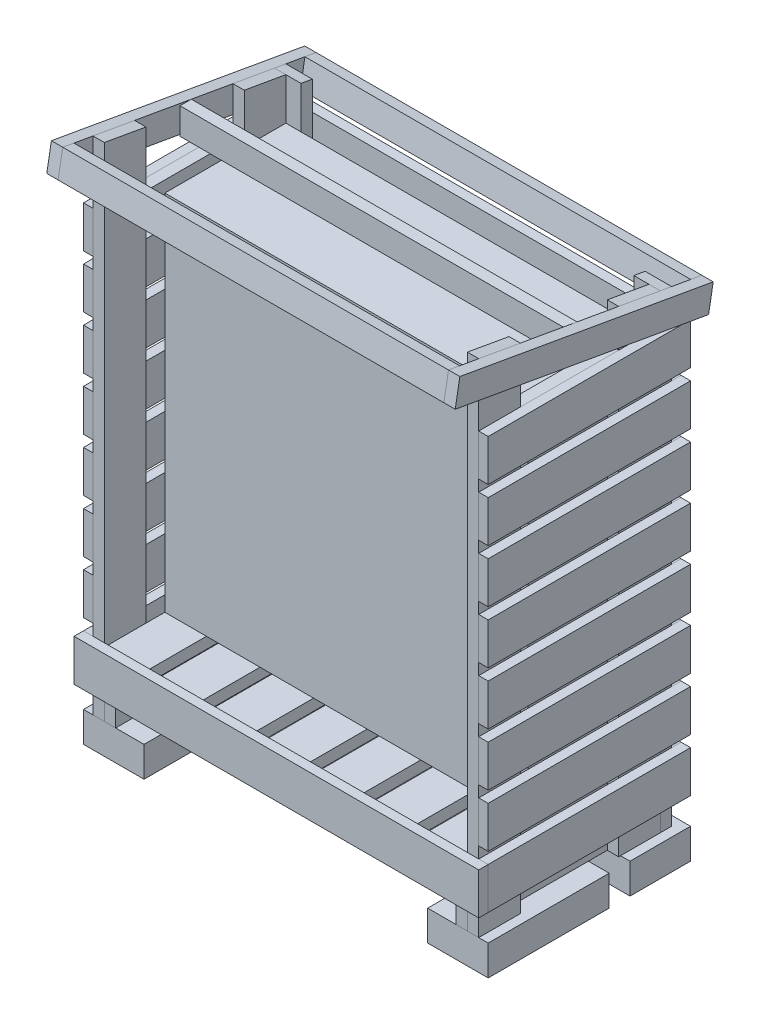
SolidWorks part; units mm, degrees
other "Wood"
ref_plane "Front Plane" through (0, 0, 0) normal (0, 0, 1) x (1, 0, 0)
ref_plane "Top Plane" through (0, 0, 0) normal (0, 1, 0) x (1, 0, 0)
ref_plane "Right Plane" through (0, 0, 0) normal (1, 0, 0) x (0, 0, -1)
sketch "Sketch4" plane through (0, 0, 0) normal (0, 1, 0) x (1, 0, 0)
  line L0 (-609.6, 304.8) -> (609.6, -304.8) construction
  line L1 (-609.6, 304.8) -> (609.6, 304.8)
  line L2 (-609.6, 304.8) -> (-609.6, 266.7)
  line L3 (-609.6, 266.7) -> (609.6, 266.7)
  line L4 (609.6, 304.8) -> (609.6, 266.7)
  line L5 (-609.6, -266.7) -> (609.6, -266.7)
  line L6 (-609.6, -266.7) -> (-609.6, -304.8)
  line L7 (-609.6, -304.8) -> (609.6, -304.8)
  line L8 (609.6, -266.7) -> (609.6, -304.8)
  line L10 (609.6, 304.8) -> (571.5, 304.8)
  line L11 (609.6, 304.8) -> (609.6, -304.8)
  line L12 (609.6, -304.8) -> (571.5, -304.8)
  line L13 (571.5, 304.8) -> (571.5, -304.8)
  line L14 (-609.6, 304.8) -> (-571.5, 304.8)
  line L15 (-609.6, 304.8) -> (-609.6, -304.8)
  line L16 (-609.6, -304.8) -> (-571.5, -304.8)
  line L17 (-571.5, 304.8) -> (-571.5, -304.8)
  point P8 (0, 0)
  dimension "D1" = 609.6
  dimension "D2" = 38.1
  dimension "D3" = 1219.2
sketch "Sketch5" plane through (0, 0, 0) normal (0, 1, 0) x (1, 0, 0)
  line L0 (-609.6, 304.8) -> (-571.5, 304.8) construction
  line L1 (-609.6, -304.8) -> (-571.5, -304.8) construction
  line L2 (609.6, -304.8) -> (571.5, -304.8) construction
  line L3 (609.6, 304.8) -> (571.5, 304.8) construction
  line L4 (609.6, 304.8) -> (609.6, -304.8) construction
  line L5 (571.5, 304.8) -> (571.5, -304.8) construction
  line L6 (-609.6, 304.8) -> (-609.6, -304.8) construction
  line L7 (-571.5, 304.8) -> (-571.5, -304.8) construction
  line L8 (-609.6, 304.8) -> (-571.5, 304.8)
  line L9 (-609.6, -304.8) -> (-571.5, -304.8)
  line L10 (609.6, -304.8) -> (571.5, -304.8)
  line L11 (609.6, 304.8) -> (571.5, 304.8)
  line L12 (609.6, 304.8) -> (609.6, -304.8)
  line L13 (571.5, 304.8) -> (571.5, -304.8)
  line L14 (-609.6, 304.8) -> (-609.6, -304.8)
  line L15 (-571.5, 304.8) -> (-571.5, -304.8)
extrude "Boss-Extrude2" add sketch "Sketch5" against normal blind 88.9
sketch "Sketch6" plane through (0, 0, 0) normal (0, 1, 0) x (1, 0, 0)
  line L0 (-609.6, -266.7) -> (-609.6, -304.8) construction
  line L1 (-609.6, -304.8) -> (609.6, -304.8) construction
  line L2 (-609.6, -266.7) -> (609.6, -266.7) construction
  line L3 (609.6, -266.7) -> (609.6, -304.8) construction
  line L4 (609.6, 304.8) -> (609.6, 266.7) construction
  line L5 (-609.6, 304.8) -> (-609.6, 266.7) construction
  line L6 (-609.6, 266.7) -> (609.6, 266.7) construction
  line L7 (-609.6, 304.8) -> (609.6, 304.8) construction
  line L8 (-609.6, -266.7) -> (-609.6, -304.8)
  line L9 (-609.6, -304.8) -> (609.6, -304.8)
  line L10 (-609.6, -266.7) -> (609.6, -266.7)
  line L11 (609.6, -266.7) -> (609.6, -304.8)
  line L12 (609.6, 304.8) -> (609.6, 266.7)
  line L13 (-609.6, 304.8) -> (-609.6, 266.7)
  line L14 (-609.6, 266.7) -> (609.6, 266.7)
  line L15 (-609.6, 304.8) -> (609.6, 304.8)
extrude "Boss-Extrude3" add sketch "Sketch6" along normal blind 88.9 separate body
sketch "Sketch7" plane through (0, 88.9, 0) normal (0, 1, 0) x (1, 0, 0)
  line L0 (-609.6, -304.8) -> (609.6, -304.8) construction
  line L1 (-609.6, 304.8) -> (-469.9, 304.8)
  line L2 (-609.6, 304.8) -> (-609.6, -304.8)
  line L3 (-609.6, -304.8) -> (-469.9, -304.8)
  line L4 (-469.9, 304.8) -> (-469.9, -304.8)
  line L5 (-429.6918, 304.8) -> (-289.9918, 304.8)
  line L6 (-429.6918, 304.8) -> (-429.6918, -304.8)
  line L7 (-429.6918, -304.8) -> (-289.9918, -304.8)
  line L8 (-289.9918, 304.8) -> (-289.9918, -304.8)
  line L9 (-249.7836, 304.8) -> (-110.0836, 304.8)
  line L10 (-249.7836, 304.8) -> (-249.7836, -304.8)
  line L11 (-249.7836, -304.8) -> (-110.0836, -304.8)
  line L12 (-110.0836, 304.8) -> (-110.0836, -304.8)
  line L13 (-69.8754, 304.8) -> (69.8246, 304.8)
  line L14 (-69.8754, 304.8) -> (-69.8754, -304.8)
  line L15 (-69.8754, -304.8) -> (69.8246, -304.8)
  line L16 (69.8246, 304.8) -> (69.8246, -304.8)
  line L17 (110.0328, 304.8) -> (249.7328, 304.8)
  line L18 (110.0328, 304.8) -> (110.0328, -304.8)
  line L19 (110.0328, -304.8) -> (249.7328, -304.8)
  line L20 (249.7328, 304.8) -> (249.7328, -304.8)
  line L21 (289.941, 304.8) -> (429.641, 304.8)
  line L22 (289.941, 304.8) -> (289.941, -304.8)
  line L23 (289.941, -304.8) -> (429.641, -304.8)
  line L24 (429.641, 304.8) -> (429.641, -304.8)
  line L25 (469.8492, 304.8) -> (609.5492, 304.8)
  line L26 (469.8492, 304.8) -> (469.8492, -304.8)
  line L27 (469.8492, -304.8) -> (609.5492, -304.8)
  line L28 (609.5492, 304.8) -> (609.5492, -304.8)
  line L29 (-609.6, 304.8) -> (-429.6918, 304.8) construction
  dimension "D1" = 139.7
  dimension "D3" = 179.9082
  dimension "D2" = 7
extrude "Boss-Extrude4" add sketch "Sketch7" along normal blind 38.1 separate body
sketch "Sketch10" plane through (0, -88.9, 0) normal (0, -1, 0) x (1, 0, 0)
  line L1 (-609.6, 304.8) -> (-647.7, 304.8)
  line L2 (-609.6, 304.8) -> (-609.6, 165.1)
  line L3 (-609.6, 165.1) -> (-647.7, 165.1)
  line L4 (-647.7, 304.8) -> (-647.7, 165.1)
  line L5 (-609.6, -304.8) -> (-647.7, -304.8)
  line L6 (-609.6, -304.8) -> (-609.6, -165.1)
  line L7 (-609.6, -165.1) -> (-647.7, -165.1)
  line L8 (-647.7, -304.8) -> (-647.7, -165.1)
  line L9 (609.6, 304.8) -> (647.7, 304.8)
  line L10 (609.6, 304.8) -> (609.6, 165.1)
  line L11 (609.6, 165.1) -> (647.7, 165.1)
  line L12 (647.7, 304.8) -> (647.7, 165.1)
  line L13 (609.6, -304.8) -> (647.7, -304.8)
  line L14 (609.6, -304.8) -> (609.6, -165.1)
  line L15 (609.6, -165.1) -> (647.7, -165.1)
  line L16 (647.7, -304.8) -> (647.7, -165.1)
  dimension "D1" = 38.1
  dimension "D2" = 139.7
extrude "Boss-Extrude7" add sketch "Sketch10" against normal blind 1828.8 separate body
sketch "Sketch16" plane through (0, -88.9, 0) normal (0, -1, 0) x (1, 0, 0)
  line L1 (-647.7, -304.8) -> (-558.8, -304.8)
  line L2 (-647.7, -304.8) -> (-647.7, -342.9)
  line L3 (-647.7, -342.9) -> (-558.8, -342.9)
  line L4 (-558.8, -304.8) -> (-558.8, -342.9)
  line L5 (647.7, -304.8) -> (558.8, -304.8)
  line L6 (647.7, -304.8) -> (647.7, -342.9)
  line L7 (647.7, -342.9) -> (558.8, -342.9)
  line L8 (558.8, -304.8) -> (558.8, -342.9)
  dimension "D1" = 38.1
  dimension "D2" = 88.9
extrude "Boss-Extrude11" add sketch "Sketch16" against normal blind 1828.8 separate body
sketch "Sketch12" plane through (0, 127, 0) normal (0, 1, 0) x (1, 0, 0)
  line L0 (609.5492, -304.8) -> (609.5492, 304.8) construction
  line L1 (-609.6, 304.8) -> (609.5492, 304.8)
  line L2 (-609.6, 304.8) -> (-609.6, -101.6)
  line L3 (-609.6, -101.6) -> (609.5492, -101.6)
  line L4 (609.5492, 304.8) -> (609.5492, -101.6)
  dimension "D1" = 406.4
extrude "Boss-Extrude8" add sketch "Sketch12" along normal blind 1219.2 separate body
sketch "Sketch13" plane through (647.7, 0, 0) normal (1, 0, 0) x (0, 0, -1)
  line L0 (-101.6, 1346.2) -> (304.8, 1346.2) construction
  line L1 (-101.6, 1346.2) -> (304.8, 1346.2) construction
  line L2 (429.0627, 1375.0891) -> (-421.8373, 1525.1258)
  line L3 (-304.8, 1739.9) -> (-304.8, -88.9) construction
  line L6 (-406.4, 1612.6752) -> (444.5, 1462.6385)
  line L8 (-406.4, 1612.6752) -> (-421.8373, 1525.1258)
  line L9 (304.8, 1739.9) -> (304.8, -88.9) construction
  line L10 (444.5, 1462.6385) -> (429.0627, 1375.0891)
  line L11 (304.8, 1739.9) -> (304.8, -88.9) construction
  point P6 (304.8, 1397)
  dimension "D1" = 88.9
  dimension "D2" = 50.8
  dimension "D3" = 10
  dimension "D4" = 101.6
  dimension "D5" = 139.7
  dimension "D6" = 864.0265
extrude "Boss-Extrude9" add sketch "Sketch13" along normal blind 38.1 separate body
mirror "Mirror1" about plane through (0, 0, 0) normal (1, 0, 0) of bodies 126
sketch "Sketch14" plane through (647.7, 0, 0) normal (1, 0, 0) x (0, 0, -1)
  line L13 (-304.8, 1739.9) -> (-304.8, 1594.7604)
  line L14 (-304.8, 1739.9) -> (-304.8, -88.9) construction
  line L15 (444.5, 1462.6385) -> (-406.4, 1612.6752) construction
  line L16 (-304.8, 1594.7604) -> (342.9, 1480.5534)
  line L17 (342.9, 1739.9) -> (342.9, -88.9) construction
  line L18 (342.9, 1480.5534) -> (342.9, 1739.9)
  line L19 (342.9, 1739.9) -> (-304.8, 1739.9)
extrude "Cut-Extrude1" cut sketch "Sketch14" against normal through all
sketch "Sketch15" plane through (-647.7, 0, 0) normal (1, 0, 0) x (0, 0, -1)
  line L0 (-406.4, 1612.6752) -> (-421.8373, 1525.1258)
  line L1 (-421.8373, 1525.1258) -> (-384.3161, 1518.5098)
  line L2 (-421.8373, 1525.1258) -> (429.0627, 1375.0891) construction
  line L3 (-384.3161, 1518.5098) -> (-368.8788, 1606.0592)
  line L4 (444.5, 1462.6385) -> (-406.4, 1612.6752) construction
  line L5 (-368.8788, 1606.0592) -> (-406.4, 1612.6752)
  line L6 (444.5, 1462.6385) -> (406.9788, 1469.2545)
  line L7 (406.9788, 1469.2545) -> (391.5415, 1381.7051)
  line L8 (391.5415, 1381.7051) -> (429.0627, 1375.0891)
  line L9 (429.0627, 1375.0891) -> (444.5, 1462.6385) construction
  line L10 (429.0627, 1375.0891) -> (444.5, 1462.6385)
  line L21 (25.4, 1536.5372) -> (-12.7, 1536.5372)
  line L22 (25.4, 1536.5372) -> (25.4, 1447.6372)
  line L23 (25.4, 1447.6372) -> (-12.7, 1447.6372)
  line L24 (-12.7, 1536.5372) -> (-12.7, 1447.6372)
  dimension "D1" = 38.1
  dimension "D2" = 152.4
extrude "Boss-Extrude10" add sketch "Sketch15" along normal up to surface (1295.4 mm away) separate body up to face at (647.7, 1493.8822, -11.3313)
sketch "Sketch18" plane through (0, 0, -342.9) normal (0, 0, -1) x (-1, 0, 0)
  line L0 (-647.7, 1480.5534) -> (-647.7, -88.9) construction
  line L1 (-647.7, 0) -> (647.7, 0)
  line L2 (-647.7, 0) -> (-647.7, 139.7)
  line L3 (-647.7, 139.7) -> (647.7, 139.7)
  line L4 (647.7, 0) -> (647.7, 139.7)
  line L5 (647.7, 1480.5534) -> (647.7, -88.9) construction
  line L6 (-647.7, 889) -> (647.7, 889)
  line L7 (-647.7, 889) -> (-647.7, 1028.7)
  line L24 (-647.7, 1028.7) -> (647.7, 1028.7)
  line L25 (-558.8, -88.9) -> (-647.7, -88.9) construction
  line L26 (-647.7, 177.8) -> (647.7, 177.8)
  line L27 (-647.7, 177.8) -> (-647.7, 317.5)
  line L28 (-647.7, 317.5) -> (647.7, 317.5)
  line L29 (647.7, 177.8) -> (647.7, 317.5)
  line L30 (-647.7, 355.6) -> (647.7, 355.6)
  line L31 (-647.7, 355.6) -> (-647.7, 495.3)
  line L32 (-647.7, 495.3) -> (647.7, 495.3)
  line L33 (647.7, 355.6) -> (647.7, 495.3)
  line L34 (-647.7, 533.4) -> (647.7, 533.4)
  line L35 (-647.7, 533.4) -> (-647.7, 673.1)
  line L36 (-647.7, 673.1) -> (647.7, 673.1)
  line L37 (647.7, 533.4) -> (647.7, 673.1)
  line L38 (-647.7, 711.2) -> (647.7, 711.2)
  line L39 (-647.7, 711.2) -> (-647.7, 850.9)
  line L40 (-647.7, 850.9) -> (647.7, 850.9)
  line L41 (647.7, 711.2) -> (647.7, 850.9)
  line L42 (-647.7, 0) -> (-647.7, 177.8) construction
  line L43 (647.7, 889) -> (647.7, 1028.7)
  line L44 (-647.7, 1066.8) -> (647.7, 1066.8)
  line L45 (-647.7, 1066.8) -> (-647.7, 1206.5)
  line L46 (-647.7, 1206.5) -> (647.7, 1206.5)
  line L47 (647.7, 1066.8) -> (647.7, 1206.5)
  line L48 (-647.7, 1244.6) -> (647.7, 1244.6)
  line L49 (-647.7, 1244.6) -> (-647.7, 1384.3)
  line L50 (-647.7, 1384.3) -> (647.7, 1384.3)
  line L51 (647.7, 1244.6) -> (647.7, 1384.3)
  dimension "D1" = 139.7
  dimension "D3" = 88.9
  dimension "D4" = 177.8
  dimension "D2" = 8
extrude "Boss-Extrude12" add sketch "Sketch18" along normal blind 31.75 separate body
sketch "Sketch20" plane through (647.7, 0, 0) normal (1, 0, 0) x (0, 0, -1)
  line L0 (-304.8, 1594.7604) -> (-304.8, -88.9) construction
  line L1 (374.65, 139.7) -> (-304.8, 139.7)
  line L2 (374.65, 139.7) -> (374.65, 0)
  line L3 (374.65, 0) -> (-304.8, 0)
  line L4 (-304.8, 139.7) -> (-304.8, 0)
  line L5 (374.65, 711.2) -> (342.9, 711.2) construction
  line L6 (374.65, 317.5) -> (-304.8, 317.5)
  line L7 (374.65, 317.5) -> (374.65, 177.8)
  line L8 (374.65, 177.8) -> (-304.8, 177.8)
  line L9 (-304.8, 317.5) -> (-304.8, 177.8)
  line L10 (374.65, 495.3) -> (-304.8, 495.3)
  line L11 (374.65, 495.3) -> (374.65, 355.6)
  line L12 (374.65, 355.6) -> (-304.8, 355.6)
  line L13 (-304.8, 495.3) -> (-304.8, 355.6)
  line L14 (374.65, 673.1) -> (-304.8, 673.1)
  line L15 (374.65, 673.1) -> (374.65, 533.4)
  line L16 (374.65, 533.4) -> (-304.8, 533.4)
  line L17 (-304.8, 673.1) -> (-304.8, 533.4)
  line L18 (374.65, 850.9) -> (-304.8, 850.9)
  line L19 (374.65, 850.9) -> (374.65, 711.2)
  line L20 (374.65, 711.2) -> (-304.8, 711.2)
  line L21 (-304.8, 850.9) -> (-304.8, 711.2)
  line L22 (374.65, 533.4) -> (342.9, 533.4) construction
  line L23 (374.65, 355.6) -> (342.9, 355.6) construction
  line L24 (374.65, 177.8) -> (342.9, 177.8) construction
  line L26 (374.65, 1028.7) -> (-304.8, 1028.7)
  line L27 (374.65, 1028.7) -> (374.65, 889)
  line L28 (374.65, 889) -> (-304.8, 889)
  line L29 (-304.8, 1028.7) -> (-304.8, 889)
  line L30 (374.65, 1206.5) -> (-304.8, 1206.5)
  line L31 (374.65, 1206.5) -> (374.65, 1066.8)
  line L32 (374.65, 1066.8) -> (-304.8, 1066.8)
  line L33 (-304.8, 1206.5) -> (-304.8, 1066.8)
  line L34 (374.65, 1384.3) -> (-304.8, 1384.3)
  line L35 (374.65, 1384.3) -> (374.65, 1244.6)
  line L36 (374.65, 1244.6) -> (-304.8, 1244.6)
  line L37 (-304.8, 1384.3) -> (-304.8, 1244.6)
extrude "Boss-Extrude13" add sketch "Sketch20" along normal blind 31.75 separate body
mirror "Mirror2" about plane through (0, 0, 0) normal (1, 0, 0) of bodies 153 152 151 150 149 169 170 171
sketch "Sketch21" plane through (0, -88.9, 0) normal (0, -1, 0) x (1, 0, 0)
  line L1 (-679.45, 304.8) -> (-476.25, 304.8)
  line L2 (-679.45, 304.8) -> (-679.45, -101.6)
  line L3 (-679.45, -101.6) -> (-476.25, -101.6)
  line L4 (-476.25, 304.8) -> (-476.25, -101.6)
  line L5 (679.45, 304.8) -> (476.25, 304.8)
  line L6 (679.45, 304.8) -> (679.45, -101.6)
  line L7 (679.45, -101.6) -> (476.25, -101.6)
  line L8 (476.25, 304.8) -> (476.25, -101.6)
  line L9 (-679.45, -374.65) -> (-273.05, -374.65)
  line L10 (-679.45, -374.65) -> (-679.45, -171.45)
  line L11 (-679.45, -171.45) -> (-273.05, -171.45)
  line L12 (-273.05, -374.65) -> (-273.05, -171.45)
  line L13 (679.45, -374.65) -> (273.05, -374.65)
  line L14 (679.45, -374.65) -> (679.45, -171.45)
  line L15 (679.45, -171.45) -> (273.05, -171.45)
  line L16 (273.05, -374.65) -> (273.05, -171.45)
  dimension "D1" = 203.2
  dimension "D2" = 406.4
extrude "Boss-Extrude14" add sketch "Sketch21" along normal blind 101.6 separate body
sketch "Sketch22" plane through (0, 0, 304.8) normal (0, 0, 1) x (1, 0, 0)
  line L0 (679.45, 139.7) -> (679.45, 0) construction
  line L1 (-679.45, 139.7) -> (679.45, 139.7)
  line L2 (-679.45, 139.7) -> (-679.45, 0)
  line L3 (-679.45, 0) -> (679.45, 0)
  line L4 (679.45, 139.7) -> (679.45, 0)
extrude "Boss-Extrude15" add sketch "Sketch22" along normal blind 31.75 separate body
sketch "Sketch23" plane through (0, 0, -165.1) normal (0, 0, 1) x (1, 0, 0)
  line L0 (-609.6, 1511.9043) -> (-609.6, -88.9) construction
  line L1 (-647.7, 1384.3) -> (-609.6, 1384.3)
  line L2 (-647.7, 1384.3) -> (-647.7, 1295.4)
  line L3 (-647.7, 1295.4) -> (-609.6, 1295.4)
  line L4 (-609.6, 1384.3) -> (-609.6, 1295.4)
  line L5 (609.6, 1511.9043) -> (609.6, -88.9) construction
  line L6 (647.7, 1384.3) -> (609.6, 1384.3)
  line L7 (647.7, 1384.3) -> (647.7, 1295.4)
  line L8 (647.7, 1295.4) -> (609.6, 1295.4)
  line L9 (609.6, 1384.3) -> (609.6, 1295.4)
  point P4 (0, 0)
  point P6 (0, 0)
  point P9 (0, 0)
  dimension "D1" = 88.9
extrude "Boss-Extrude16" add sketch "Sketch23" along normal up to surface (330.2 mm away) separate body up to face at (-628.65, 740.6137, 165.1)
